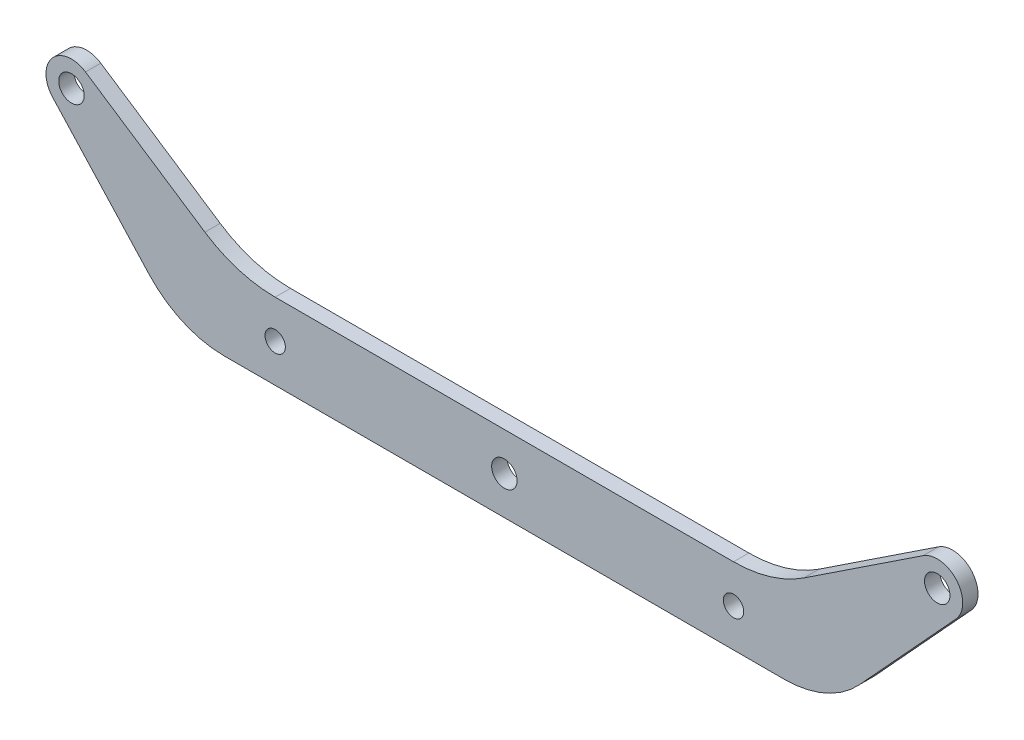
SolidWorks part; units mm, degrees
material "Thornel Mat VMA"
ref_plane "前视基准面" through (0, 0, 0) normal (0, 0, 1) x (1, 0, 0)
ref_plane "上视基准面" through (0, 0, 0) normal (0, 1, 0) x (1, 0, 0)
ref_plane "右视基准面" through (0, 0, 0) normal (1, 0, 0) x (0, 0, -1)
sketch "草图1" plane through (0, 0, 0) normal (0, 0, 1) x (1, 0, 0)
  line L0 (-85, 0) -> (85, 0) construction
  line L1 (0, 55.7504) -> (0, -72.112) construction
  line L2 (-55, -30.5) -> (0, -30.5)
  line L3 (-45, -15.5) -> (0, -15.5)
  line L4 (-82.2402, 4.1694) -> (-58.7989, -11.3468)
  line L5 (-88.6834, -3.3812) -> (-69.7337, -24.0248)
  line L6 (88.6834, -3.3812) -> (69.7337, -24.0248)
  line L7 (82.2402, 4.1694) -> (58.7989, -11.3468)
  line L8 (45, -23) -> (-45, -23) construction
  line L9 (0, -15.5) -> (45, -15.5)
  line L10 (0, -30.5) -> (55, -30.5)
  arc A0 (-82.2402, 4.1694) -> (-88.6834, -3.3812) centre (-85, 0) ccw
  arc A2 (-58.7989, -11.3468) -> (-45, -15.5) centre (-45, 9.5) ccw
  circle A3 centre (85, 0) radius 2.5
  arc A4 (82.2402, 4.1694) -> (88.6834, -3.3812) centre (85, 0) cw
  arc A5 (-69.7337, -24.0248) -> (-55, -30.5) centre (-55, -10.5) ccw
  circle A6 centre (-85, 0) radius 2.5
  circle A7 centre (-85, 0) radius 5 construction
  arc A9 (69.7337, -24.0248) -> (55, -30.5) centre (55, -10.5) cw
  arc A10 (58.7989, -11.3468) -> (45, -15.5) centre (45, 9.5) cw
  circle A11 centre (0, -23) radius 2.5
  circle A12 centre (-45, -23) radius 2
  circle A13 centre (45, -23) radius 2
  point P0 (0.4758, -17.5)
  dimension "D2" = 5
  dimension "D7" = 55
  dimension "D9" = 45
  dimension "D11" = 5
  dimension "D12" = 20
  dimension "D6" = 25
  dimension "D13" = 7.5
  dimension "D3" = 5
  dimension "D16" = 4
  dimension "D4" = 15
  dimension "D5" = 23
  dimension "D8" = 85
  dimension "D15" = 45
extrude "凸台-拉伸1" add sketch "草图1" along normal blind 3
ref_plane "基准面1" through (0, 2.5, 0) normal (0, -1, 0) x (-1, 0, 0)
